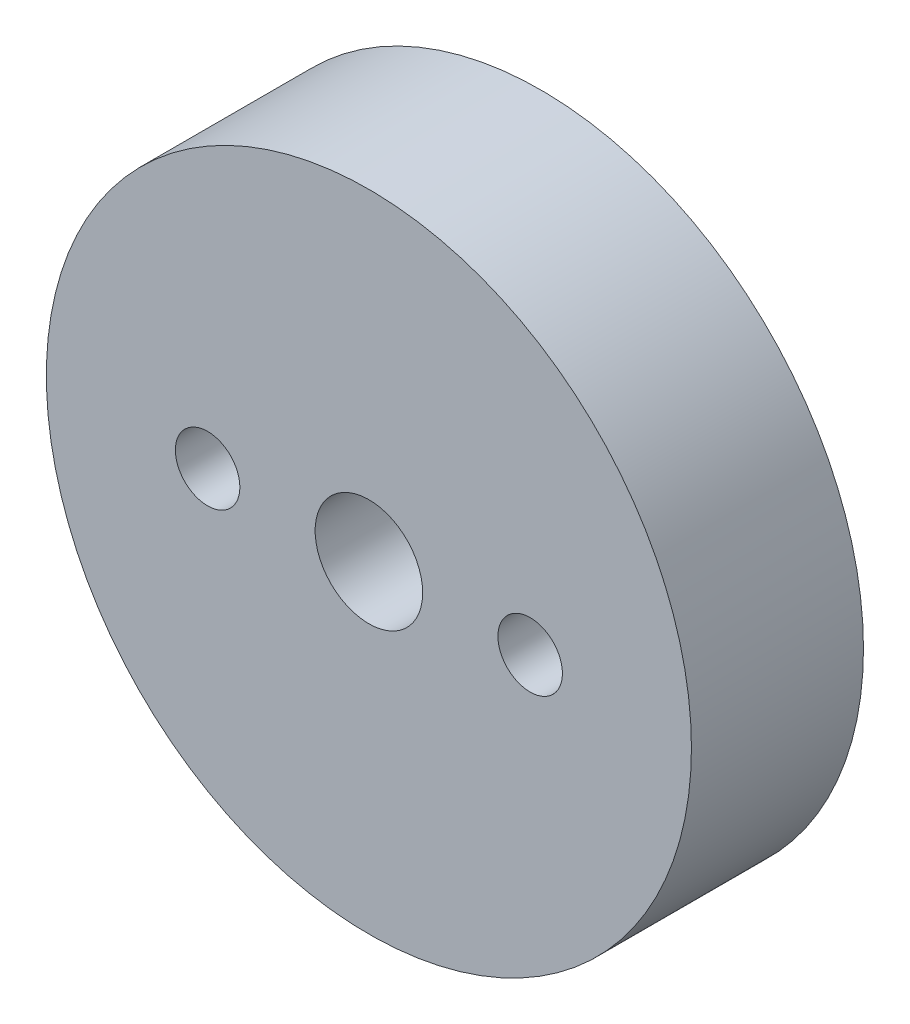
SolidWorks part; units mm, degrees
ref_plane "Front Plane" through (0, 0, 0) normal (0, 0, 1) x (1, 0, 0)
ref_plane "Top Plane" through (0, 0, 0) normal (0, 1, 0) x (1, 0, 0)
ref_plane "Right Plane" through (0, 0, 0) normal (1, 0, 0) x (0, 0, -1)
sketch "Sketch1" plane through (0, 0, 0) normal (0, 0, 1) x (1, 0, 0)
  circle A0 centre (0, 0) radius 15
  circle A1 centre (0, 0) radius 2.5
  circle A2 centre (7.5, 0) radius 1.5
  circle A3 centre (-7.5, 0) radius 1.5
extrude "Boss-Extrude1" add sketch "Sketch1" along normal blind 8
